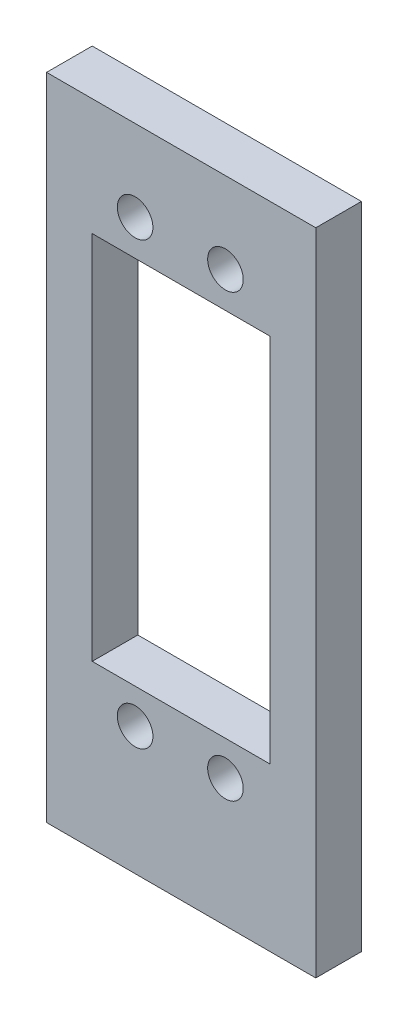
SolidWorks part; units mm, degrees
ref_plane "Alzado" through (0, 0, 0) normal (0, 0, 1) x (1, 0, 0)
ref_plane "Planta" through (0, 0, 0) normal (0, 1, 0) x (1, 0, 0)
ref_plane "Vista lateral" through (0, 0, 0) normal (1, 0, 0) x (0, 0, -1)
sketch "Croquis1" plane through (0, 0, 0) normal (0, 0, 1) x (1, 0, 0)
  line L1 (9.75, -20.3) -> (9.75, 20.3)
  line L2 (9.75, 20.3) -> (-9.75, 20.3)
  line L3 (-14.75, 33.1) -> (14.75, 33.1)
  line L4 (-9.75, -20.3) -> (-9.75, 20.3)
  line L5 (9.75, -20.3) -> (-9.75, -20.3)
  line L6 (14.75, 33.1) -> (14.75, 0)
  line L8 (-14.75, 33.1) -> (-14.75, 0)
  line L9 (-14.75, 0) -> (-14.75, -38.1)
  line L10 (-14.75, -38.1) -> (14.75, -38.1)
  line L11 (14.75, -38.1) -> (14.75, 0)
  dimension "D1" = 19.5
  dimension "D2" = 40.6
extrude "Saliente-Extruir2" add sketch "Croquis1" along normal blind 5
sketch "Croquis3" plane through (0, 0, 5) normal (0, 0, 1) x (1, 0, 0)
  circle A0 centre (-5.05, 24.2) radius 1.95 construction
  circle A1 centre (-5.05, 24.2) radius 1.95
  circle A2 centre (4.85, 24.2) radius 1.95 construction
  circle A3 centre (-5.05, -24.1) radius 1.95 construction
  circle A4 centre (4.85, -24.1) radius 1.95 construction
  circle A5 centre (4.85, 24.2) radius 1.95
  circle A6 centre (-5.05, -24.1) radius 1.95
  circle A7 centre (4.85, -24.1) radius 1.95
extrude "Cortar-Extruir1" cut sketch "Croquis3" against normal blind 10
